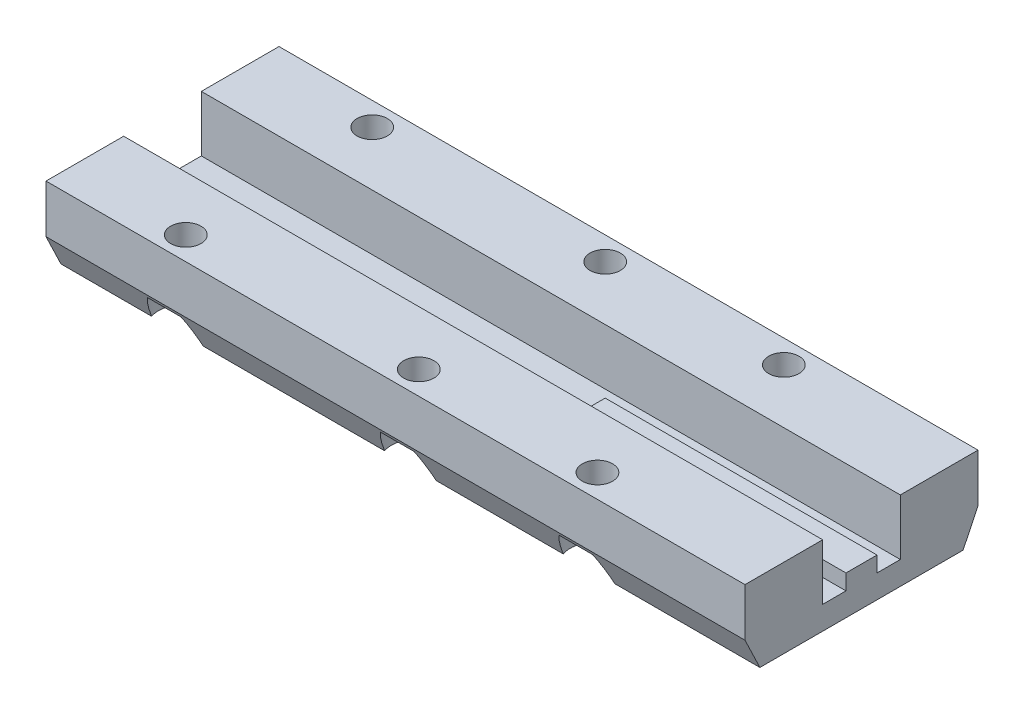
SolidWorks part; units mm, degrees
ref_plane "정면" through (0, 0, 0) normal (0, 0, 1) x (1, 0, 0)
ref_plane "윗면" through (0, 0, 0) normal (0, 1, 0) x (1, 0, 0)
ref_plane "우측면" through (0, 0, 0) normal (1, 0, 0) x (0, 0, -1)
sketch "스케치1" plane through (0, 0, 0) normal (1, 0, 0) x (0, 0, -1)
  line L0 (0, 0) -> (0, -19.6739) construction
  line L1 (0, 0) -> (-29.5436, 0) construction
  line L2 (-15, 0) -> (-15, -6.2)
  line L3 (-5, 0) -> (-5, -7.2)
  line L4 (-5, -7.2) -> (-1.95, -7.2)
  line L5 (-1.95, -7.2) -> (-1.95, -10.2)
  line L6 (-1.95, -10.2) -> (-13.0811, -10.2)
  line L7 (-13.0811, -10.2) -> (-15, -6.2)
  line L8 (-15, 0) -> (-5, 0)
  line L9 (13.0811, -10.2) -> (15, -6.2)
  line L10 (15, 0) -> (5, 0)
  line L11 (1.95, -10.2) -> (13.0811, -10.2)
  line L12 (1.95, -7.2) -> (1.95, -10.2)
  line L13 (5, -7.2) -> (1.95, -7.2)
  line L14 (5, 0) -> (5, -7.2)
  line L15 (15, 0) -> (15, -6.2)
  line L16 (-7.55, 0) -> (-22.5, 0) construction
  dimension "D1" = 7.2
  dimension "D2" = 5
  dimension "D3" = 3
  dimension "D4" = 10
  dimension "D5" = 3.9
extrude "보스-돌출1" add sketch "스케치1" along normal blind 90
sketch "스케치3" plane through (0, -10.2, 0) normal (0, -1, 0) x (1, 0, 0)
  line L0 (15, 12) -> (45, 12) construction
  line L1 (45, 12) -> (68, 12) construction
  line L2 (68, 12) -> (103, 12) construction
  line L4 (90, 13.0811) -> (90, 1.95) construction
  line L5 (0, 0) -> (166.614, 0) construction
  circle A0 centre (15, 12) radius 1.95
  circle A1 centre (45, 12) radius 1.95
  circle A2 centre (103, 12) radius 1.95 construction
  circle A3 centre (68, 12) radius 1.95
  circle A5 centre (68, -12) radius 1.95
  circle A6 centre (45, -12) radius 1.95
  circle A7 centre (15, -12) radius 1.95
  dimension "D1" = 3.9
  dimension "D2" = 3.9
  dimension "D3" = 3.9
  dimension "D4" = 3.9
  dimension "D5" = 30
  dimension "D6" = 22
  dimension "D7" = 35
  dimension "D8" = 23
  dimension "D9" = 12
extrude "컷-돌출1" cut sketch "스케치3" against normal through all
sketch "스케치5" plane through (0, 0, 0) normal (0, 0, 1) x (1, 0, 0)
  line L0 (90, -10.2) -> (69.6229, -10.2) construction
  line L1 (55, -5.2) -> (90, -5.2)
  line L2 (55, -5.2) -> (55, -10.2)
  line L3 (55, -10.2) -> (90, -10.2)
  line L4 (90, -5.2) -> (90, -10.2)
  line L5 (90, -6.2) -> (90, -10.2) construction
  dimension "D1" = 35
  dimension "D2" = 5
extrude "보스-돌출2" add sketch "스케치5" along normal mid plane 4
sketch "스케치7" plane through (0, -10.2, 0) normal (0, -1, 0) x (1, 0, 0)
  circle A0 centre (15, -12) radius 3.5
  circle A1 centre (45, -12) radius 3.5
  circle A2 centre (68, -12) radius 3.5
  circle A3 centre (45, 12) radius 3.5
  circle A4 centre (68, 12) radius 3.5
  circle A5 centre (15, 12) radius 3.5
  dimension "D1" = 7
  dimension "D2" = 7
  dimension "D3" = 7
  dimension "D4" = 7
  dimension "D5" = 7
  dimension "D6" = 7
extrude "컷-돌출2" cut sketch "스케치7" against normal blind 3.5
